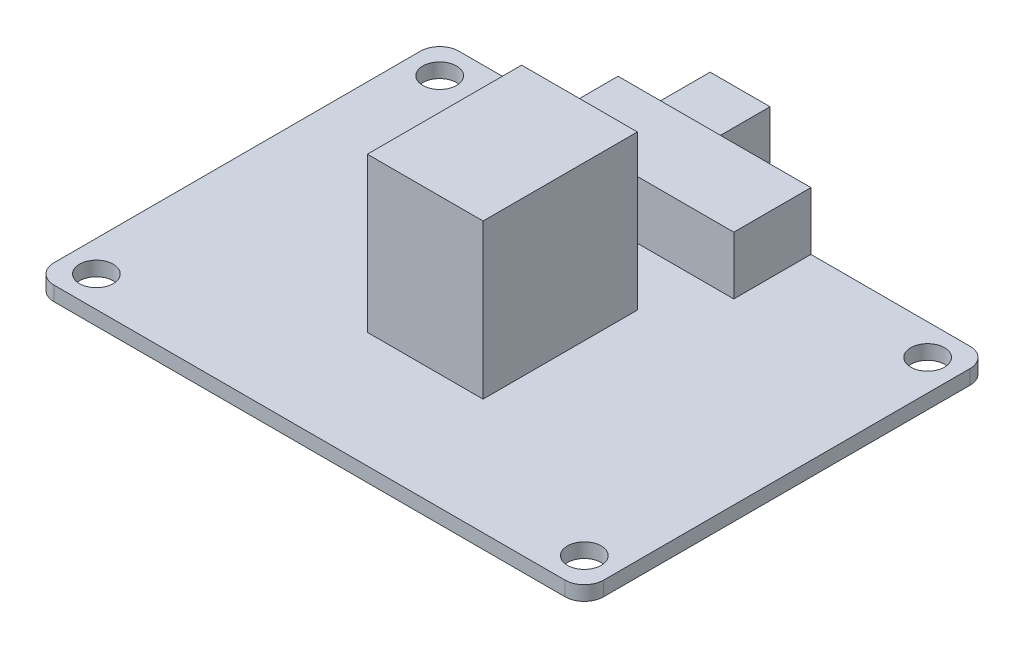
SolidWorks part; units mm, degrees
ref_plane "Front Plane" through (0, 0, 0) normal (0, 0, 1) x (1, 0, 0)
ref_plane "Top Plane" through (0, 0, 0) normal (0, 1, 0) x (1, 0, 0)
ref_plane "Right Plane" through (0, 0, 0) normal (1, 0, 0) x (0, 0, -1)
sketch "Sketch1" plane through (0, 0, 0) normal (0, 1, 0) x (1, 0, 0)
  line L1 (-28.5, -21) -> (28.5, -21)
  line L2 (-28.5, -21) -> (-28.5, 21)
  line L3 (-28.5, 21) -> (28.5, 21)
  line L4 (28.5, -21) -> (28.5, 21)
  line L5 (-28.5, -21) -> (28.5, 21) construction
  line L6 (-28.5, 21) -> (28.5, -21) construction
  point P0 (0, 0)
  dimension "D1" = 57
  dimension "D2" = 42
extrude "Boss-Extrude1" add sketch "Sketch1" along normal blind 1.5
sketch "Sketch2" plane through (0, 1.5, 0) normal (0, 1, 0) x (1, 0, 0)
  line L1 (25.3, -17.8) -> (-25.3, -17.8) construction
  line L2 (25.3, -17.8) -> (25.3, 17.8) construction
  line L3 (25.3, 17.8) -> (-25.3, 17.8) construction
  line L4 (-25.3, -17.8) -> (-25.3, 17.8) construction
  line L5 (25.3, -17.8) -> (-25.3, 17.8) construction
  line L6 (25.3, 17.8) -> (-25.3, -17.8) construction
  circle A0 centre (-25.3, 17.8) radius 1.75
  circle A1 centre (-25.3, -17.8) radius 1.75
  circle A2 centre (25.3, -17.8) radius 1.75
  circle A3 centre (25.3, 17.8) radius 1.75
  point P0 (0, 0)
  dimension "D3" = 3.5
  dimension "D1" = 35.6
  dimension "D2" = 50.6
extrude "Cut-Extrude1" cut sketch "Sketch2" against normal blind 10
sketch "Sketch3" plane through (0, 1.5, 0) normal (0, 1, 0) x (1, 0, 0)
  line L0 (28.5, 21) -> (-28.5, 21) construction
  line L1 (6, 7) -> (-6, 7)
  line L2 (6, 7) -> (6, -9)
  line L3 (6, -9) -> (-6, -9)
  line L4 (-6, 7) -> (-6, -9)
  line L5 (10, 13) -> (-10, 13)
  line L6 (10, 13) -> (10, 21)
  line L7 (10, 21) -> (-10, 21)
  line L8 (-10, 13) -> (-10, 21)
  line L9 (-28.5, 21) -> (-28.5, -21) construction
  line L10 (-18.5, 10) -> (-28.5, 10) construction
  line L11 (-18.5, 10) -> (-18.5, 0) construction
  line L12 (-18.5, 0) -> (-28.5, 0) construction
  line L13 (-28.5, 10) -> (-28.5, 0) construction
  line L14 (0, 13) -> (0, 0) construction
  line L15 (0, 0) -> (0, 7) construction
  line L16 (-28.5, -21) -> (28.5, -21) construction
  dimension "D1" = 20
  dimension "D2" = 8
  dimension "D3" = 12
  dimension "D4" = 16
  dimension "D5" = 12
  dimension "D6" = 10
  dimension "D7" = 11
extrude "Boss-Extrude2" add sketch "Sketch3" along normal blind 6
sketch "Sketch4" plane through (0, 0, -21) normal (0, 0, -1) x (-1, 0, 0)
  line L1 (0.2435, 6.6418) -> (6.4533, 6.6418)
  line L2 (0.2435, 6.6418) -> (0.2435, 1.5888)
  line L3 (0.2435, 1.5888) -> (6.4533, 1.5888)
  line L4 (6.4533, 6.6418) -> (6.4533, 1.5888)
extrude "Boss-Extrude3" add sketch "Sketch4" along normal blind 6
fillet "Fillet3" radius 2 4 edges at (-28.5, 0.75, -21) (-28.5, 0.75, 21) (28.5, 0.75, -21) (28.5, 0.75, 21)
sketch "Sketch7" plane through (0, 7.5, 0) normal (0, 1, 0) x (1, 0, 0)
  line L4 (6, -9) -> (6, 7)
  line L5 (6, 7) -> (-6, 7)
  line L6 (-6, 7) -> (-6, -9)
  line L7 (-6, -9) -> (6, -9)
  line L8 (6, -9) -> (6, 7)
  line L9 (6, 7) -> (-6, 7)
  line L10 (-6, 7) -> (-6, -9)
  line L11 (-6, -9) -> (6, -9)
  dimension "D1" = 0
extrude "Boss-Extrude6" add sketch "Sketch7" along normal blind 10
